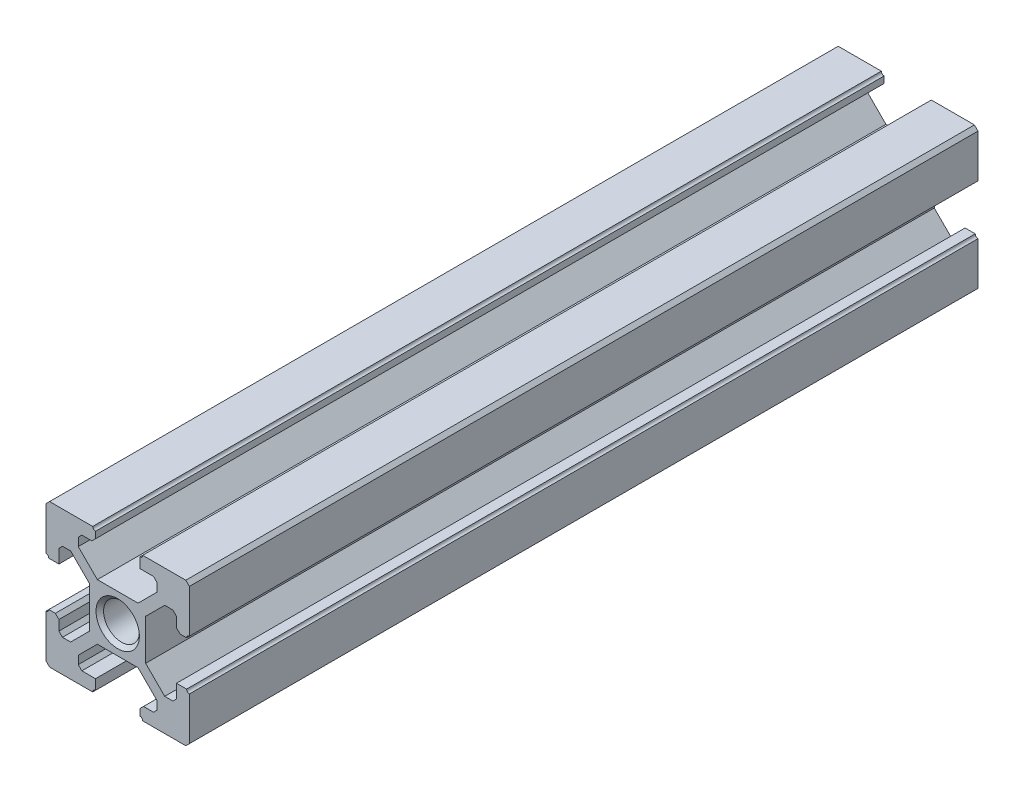
SolidWorks part; units mm, degrees
ref_plane "Front Plane" through (0, 0, 0) normal (0, 0, 1) x (1, 0, 0)
ref_plane "Top Plane" through (0, 0, 0) normal (0, 1, 0) x (1, 0, 0)
ref_plane "Right Plane" through (0, 0, 0) normal (1, 0, 0) x (0, 0, -1)
sketch "Sketch1" plane through (0, 0, 0) normal (0, 0, 1) x (1, 0, 0)
  line L0 (0, 10.7337) -> (0, 0.7337) construction
  line L1 (-9.5, 10) -> (-3.4865, 10)
  line L2 (-10, 9.5) -> (-10, 3.4865)
  line L3 (-9.5, -10) -> (-3.4865, -10)
  line L4 (10, 9.5) -> (10, 3.4865)
  line L5 (-9.75, 9.75) -> (9.75, -9.75) construction
  line L6 (-9.75, -9.75) -> (10, 10) construction
  line L7 (0, 0) -> (-10, 0) construction
  line L8 (3.1, 9.6135) -> (3.1, 8.2)
  line L9 (3.1, 8.2) -> (5, 8.2)
  line L10 (5.5, 7.7) -> (5.5, 6.5607)
  line L11 (5.5, 6.5607) -> (2.8393, 3.9)
  line L12 (2.8393, 3.9) -> (0, 3.9)
  line L13 (3.9, 2.8393) -> (3.9, 0)
  line L14 (6.5607, 5.5) -> (3.9, 2.8393)
  line L15 (9.6135, 3.1) -> (8.7, 3.1)
  line L16 (8.2, 3.6) -> (8.2, 5)
  line L17 (7.7, 5.5) -> (6.5607, 5.5)
  line L18 (3.4865, 10) -> (9.5, 10)
  line L19 (10, -3.4865) -> (10, -9.5)
  line L20 (5, 8.2) -> (5.5, 7.7)
  line L21 (8.2, 5) -> (7.7, 5.5)
  line L22 (9.5, 10) -> (10, 9.5)
  line L23 (8.7, 3.1) -> (8.2, 3.6)
  line L24 (3.9, -2.8393) -> (3.9, 0)
  line L25 (6.5607, -5.5) -> (3.9, -2.8393)
  line L26 (7.7, -5.5) -> (6.5607, -5.5)
  line L27 (8.2, -5) -> (7.7, -5.5)
  line L28 (8.2, -3.1) -> (8.2, -5)
  line L29 (9.6135, -3.1) -> (8.2, -3.1)
  line L30 (10, -3.4865) -> (10, -9.5)
  line L31 (10, -9.5) -> (9.5, -10)
  line L32 (9.5, -10) -> (3.4865, -10)
  line L33 (3.1, -9.6135) -> (3.1, -8.7)
  line L34 (3.1, -8.7) -> (3.6, -8.2)
  line L35 (3.6, -8.2) -> (5, -8.2)
  line L36 (5, -8.2) -> (5.5, -7.7)
  line L37 (5.5, -7.7) -> (5.5, -6.5607)
  line L38 (5.5, -6.5607) -> (2.8393, -3.9)
  line L39 (2.8393, -3.9) -> (0, -3.9)
  line L40 (-2.8393, -3.9) -> (0, -3.9)
  line L41 (-5.5, -6.5607) -> (-2.8393, -3.9)
  line L42 (-5.5, -7.7) -> (-5.5, -6.5607)
  line L43 (-5, -8.2) -> (-5.5, -7.7)
  line L44 (-3.1, -8.2) -> (-5, -8.2)
  line L45 (-3.1, -9.6135) -> (-3.1, -8.2)
  line L46 (-3.4865, -10) -> (-9.5, -10)
  line L47 (-9.5, -10) -> (-10, -9.5)
  line L48 (-10, -9.5) -> (-10, -3.4865)
  line L49 (-9.6135, -3.1) -> (-8.7, -3.1)
  line L50 (-8.7, -3.1) -> (-8.2, -3.6)
  line L51 (-8.2, -3.6) -> (-8.2, -5)
  line L52 (-8.2, -5) -> (-7.7, -5.5)
  line L53 (-7.7, -5.5) -> (-6.5607, -5.5)
  line L54 (-6.5607, -5.5) -> (-3.9, -2.8393)
  line L55 (-3.9, -2.8393) -> (-3.9, 0)
  line L56 (-3.9, 2.8393) -> (-3.9, 0)
  line L57 (-6.5607, 5.5) -> (-3.9, 2.8393)
  line L58 (-7.7, 5.5) -> (-6.5607, 5.5)
  line L59 (-8.2, 5) -> (-7.7, 5.5)
  line L60 (-8.2, 3.1) -> (-8.2, 5)
  line L61 (-9.6135, 3.1) -> (-8.2, 3.1)
  line L62 (-10, 3.4865) -> (-10, 9.5)
  line L63 (-10, 9.5) -> (-9.5, 10)
  line L64 (-9.5, 10) -> (-3.4865, 10)
  line L65 (-3.1, 9.6135) -> (-3.1, 8.7)
  line L66 (-3.1, 8.7) -> (-3.6, 8.2)
  line L67 (-3.6, 8.2) -> (-5, 8.2)
  line L68 (-5, 8.2) -> (-5.5, 7.7)
  line L69 (-5.5, 7.7) -> (-5.5, 6.5607)
  line L70 (-5.5, 6.5607) -> (-2.8393, 3.9)
  line L71 (-2.8393, 3.9) -> (0, 3.9)
  line L72 (3.4865, -10) -> (9.5, -10)
  line L73 (-10, -3.4865) -> (-10, -9.5)
  arc A0 (3.1, 9.6135) -> (3.4865, 10) centre (3.1, 10) ccw
  arc A1 (9.6135, 3.1) -> (10, 3.4865) centre (10, 3.1) cw
  arc A2 (9.6135, -3.1) -> (10, -3.4865) centre (10, -3.1) ccw
  arc A3 (3.1, -9.6135) -> (3.4865, -10) centre (3.1, -10) cw
  arc A4 (-3.1, -9.6135) -> (-3.4865, -10) centre (-3.1, -10) ccw
  arc A5 (-9.6135, -3.1) -> (-10, -3.4865) centre (-10, -3.1) cw
  arc A6 (-9.6135, 3.1) -> (-10, 3.4865) centre (-10, 3.1) ccw
  arc A7 (-3.1, 9.6135) -> (-3.4865, 10) centre (-3.1, 10) cw
  point P0 (0, 0)
  point P13 (5.5, 8.2)
  point P17 (3.1, 8.9068)
  point P22 (8.2, 3.1)
  point P23 (8.2, 5.5)
  point P103 (0, 0)
  dimension "D3" = 1.8
  dimension "D4" = 6.1
  dimension "D5" = 11
  dimension "D6" = 6.2
  dimension "D7" = 1.5
extrude "Boss-Extrude1" add sketch "Sketch1" along normal blind 110 contours L65 A7 L1 L63 L2 A6 L61 L60 L59 L58 L57 L56 L55 L54 L53 L52 L51 L50 L49 A5 L48 L47 L3 A4 L45 L44 L43 L42 L41 L40 L39 L38 L37 L36 L35 L34 L33 A3 L32 L31 L19 A2 L29 L28 L27 L26 L25 L24 L13 L14 L17
hole_wizard "M6x1.0 Tapped Hole1" positions "3DSketch1" profile "Sketch2" tap size "M6x1.0" standard "ANSI Metric"
sketch3d "3DSketch1"
  line L0 (3.9, -2.8393, 110) -> (3.9, 2.8393, 110) construction
  line L1 (2.8393, 3.9, 110) -> (-2.8393, 3.9, 110) construction
  point P0 (0, 0, 0)
  point P3 (0, 0, 0)
  point P5 (0, 0, 0)
  point P7 (0.9996, -8.1302, 0)
  point P9 (0, 0, 0)
  point P11 (0, 0, 110)
  dimension "D1" = 3.9
  dimension "D2" = 3.9
sketch "Sketch2" plane through (0, 0, 110) normal (1, 0, 0) x (0, -1, 0)
  line L0 (0, 0) -> (0, 30)
  line L1 (0, 30) -> (2.5, 28.4978)
  line L2 (2.5, 28.4978) -> (2.5, 0.525)
  line L3 (2.5, 0.525) -> (3.025, 0)
  line L5 (3.025, 0) -> (0, 0)
  line L6 (-2.5, 0.525) -> (-3.025, 0) construction
  line L10 (0, 30) -> (-2.5, 28.4978) construction
  line L11 (0, -6.35) -> (0, 107.95) construction
  dimension "Tap Drill Dia." = 5
  dimension "Tap Drill Depth" = 30
  dimension "Near C'Sink Dia." = 6.05
  dimension "Near C'Sink Angle" = 90
  dimension "Drill Angle" = 118
cosmetic thread "Hole Thread6" parameters "D1"=12, "D2"=6
hole_wizard "M6x1.0 Tapped Hole2" positions "3DSketch2" profile "Sketch3" tap size "M6x1.0" standard "ANSI Metric"
sketch3d "3DSketch2"
  line L0 (2.8393, 3.9, 0) -> (-2.8393, 3.9, 0) construction
  line L1 (3.9, -2.8393, 0) -> (3.9, 2.8393, 0) construction
  point P3 (0, 0, 0)
  dimension "D1" = 3.9
  dimension "D2" = 3.9
sketch "Sketch3" plane through (0, 0, 0) normal (1, 0, 0) x (0, 1, 0)
  line L0 (0, 0) -> (0, 30)
  line L1 (0, 30) -> (2.5, 28.4978)
  line L2 (2.5, 28.4978) -> (2.5, 0.525)
  line L3 (2.5, 0.525) -> (3.025, 0)
  line L5 (3.025, 0) -> (0, 0)
  line L6 (-2.5, 0.525) -> (-3.025, 0) construction
  line L10 (0, 30) -> (-2.5, 28.4978) construction
  line L11 (0, -6.35) -> (0, 107.95) construction
  dimension "Tap Drill Dia." = 5
  dimension "Tap Drill Depth" = 30
  dimension "Near C'Sink Dia." = 6.05
  dimension "Near C'Sink Angle" = 90
  dimension "Drill Angle" = 118
cosmetic thread "Hole Thread7" parameters "D1"=12, "D2"=6
